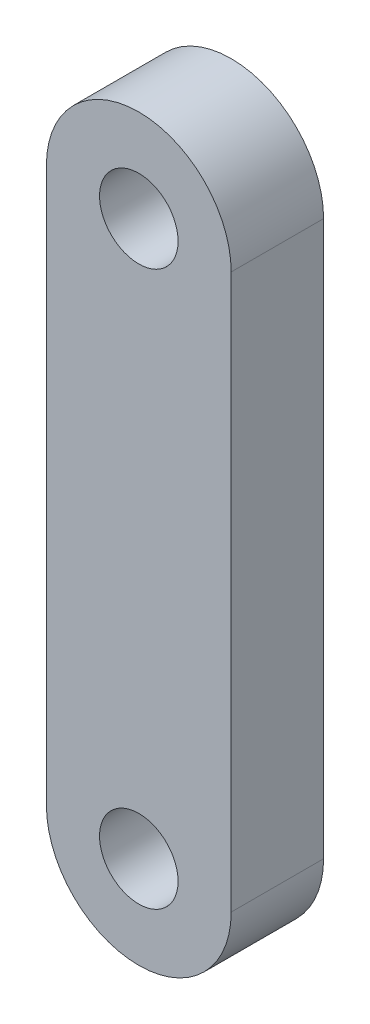
SolidWorks part; units mm, degrees
ref_plane "前视基准面" through (0, 0, 0) normal (0, 0, 1) x (1, 0, 0)
ref_plane "上视基准面" through (0, 0, 0) normal (0, 1, 0) x (1, 0, 0)
ref_plane "右视基准面" through (0, 0, 0) normal (1, 0, 0) x (0, 0, -1)
sketch "草图1" plane through (0, 0, 0) normal (0, 0, 1) x (1, 0, 0)
  line L0 (0, 0) -> (0, -24) construction
  line L2 (4, 0) -> (4, -24)
  line L3 (-4, 0) -> (-4, -24)
  arc A0 (4, 0) -> (-4, 0) centre (0, 0) ccw
  arc A1 (-4, -24) -> (4, -24) centre (0, -24) ccw
  circle A2 centre (0, 0) radius 1.7
  circle A3 centre (0, -24) radius 1.7
  point P5 (0, -12)
  dimension "D3" = 3.4
  dimension "D4" = 3.4
  dimension "D1" = 8
  dimension "D2" = 24
extrude "凸台-拉伸1" add sketch "草图1" along normal blind 4
